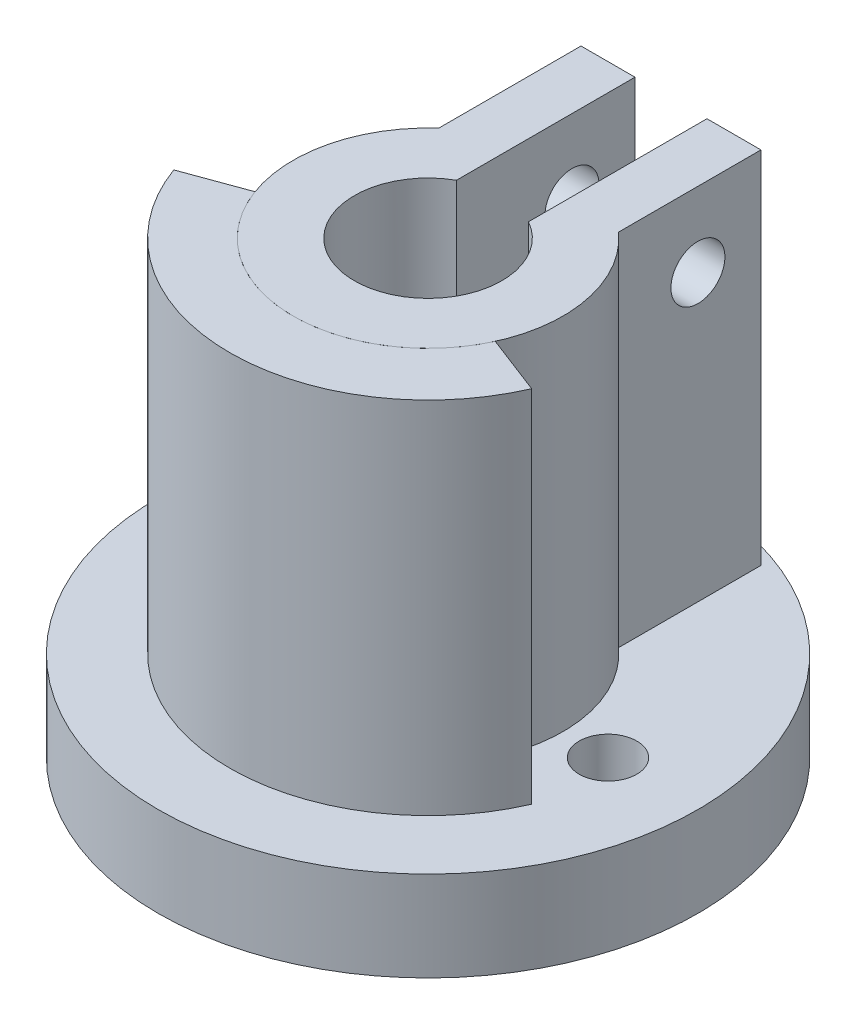
SolidWorks part; units mm, degrees
ref_plane "前视基准面" through (0, 0, 0) normal (0, 0, 1) x (1, 0, 0)
ref_plane "上视基准面" through (0, 0, 0) normal (0, 1, 0) x (1, 0, 0)
ref_plane "右视基准面" through (0, 0, 0) normal (1, 0, 0) x (0, 0, -1)
sketch "草图1" plane through (0, 0, 0) normal (0, 1, 0) x (1, 0, 0)
  circle A0 centre (0, 0) radius 15
extrude "凸台-拉伸1" add sketch "草图1" along normal blind 5
sketch "草图2" plane through (0, 5, 0) normal (0, 1, 0) x (1, 0, 0)
  circle A0 centre (0, 0) radius 7.5
  circle A1 centre (0, 0) radius 4.1
extrude "凸台-拉伸2" add sketch "草图2" along normal blind 20
sketch "草图3" plane through (0, 5, 0) normal (0, 1, 0) x (1, 0, 0)
  line L0 (0, 0) -> (10, 0)
  line L1 (0, 0) -> (-10, 0)
  circle A1 centre (10, 0) radius 1.6
  circle A2 centre (-10, 0) radius 1.6
extrude "切除-拉伸1" cut sketch "草图3" against normal through all contours A2 | A1
sketch "草图4" plane through (0, 5, 0) normal (0, 1, 0) x (1, 0, 0)
  circle A0 centre (0, 0) radius 4.1
extrude "切除-拉伸2" cut sketch "草图4" against normal through all
sketch "草图5" plane through (0, 0, 0) normal (0, 0, 1) x (1, 0, 0)
  line L0 (0, 5) -> (2, 5)
  line L1 (15, 5) -> (-15, 5) construction
  line L2 (0, 5) -> (-2, 5)
  line L3 (-2, 5) -> (2, 5)
  line L4 (-2, 5) -> (-2, 30)
  line L5 (2, 5) -> (2, 30)
  line L6 (-2, 30) -> (2, 30)
extrude "切除-拉伸3" cut sketch "草图5" against normal blind 20 contours L6 L4 L2 L0 L5
sketch3d "3D草图1"
  line L0 (-2, 25, -7.2284) -> (-2, 25, -3.5791) construction
  line L2 (2, 25, -8.5) -> (5, 25, -8.5)
  line L3 (2, 25, -8.5) -> (2, 4.704, -8.5)
  line L4 (2, 4.704, -8.5) -> (5, 4.704, -8.5)
  line L5 (5, 25, -8.5) -> (5, 4.704, -8.5)
  line L6 (-2, 25, -8.5) -> (-5, 25, -8.5)
  line L7 (-2, 25, -8.5) -> (-2, 4.022, -8.5)
  line L8 (-2, 4.022, -8.5) -> (-5, 4.022, -8.5)
  line L9 (-5, 25, -8.5) -> (-5, 4.022, -8.5)
  dimension "D1" = 8.5
sketch "草图6" plane through (0, 5, 0) normal (0, 1, 0) x (1, 0, 0)
  line L0 (0, 1.9373) -> (0, 13.8987)
extrude "凸台-拉伸3" add sketch "3D草图1" along direction (0, 0, -1) on the side against the normal blind 5 and the other way blind 3
sketch "草图8" plane through (5, 0, 0) normal (1, 0, 0) x (0, 0, -1)
  circle A0 centre (9.9967, 20.8524) radius 1.5
  point P2 (9.9967, 20.8524)
extrude "切除-拉伸4" cut sketch "草图8" against normal through all
sketch "草图13" plane through (0, 25, 0) normal (0, 1, 0) x (1, 0, 0)
  line L0 (-7.0454, -2.5713) -> (-10.3531, -3.7785)
  line L1 (6.8308, -3.0968) -> (10.1204, -4.3637)
  circle A0 centre (0, 0) radius 7.5
  circle A1 centre (0, 0) radius 11.0211
  arc M5 (-5, 5.5902) -> (5, 5.5902) centre (0, 0) ccw
extrude "凸台-拉伸4" add sketch "草图13" against normal blind 20 separate body contours L0 A1 L1 M5
sketch "草图14" plane through (0, 30, 0) normal (0, 1, 0) x (1, 0, 0)
  circle A0 centre (0, 0) radius 17
